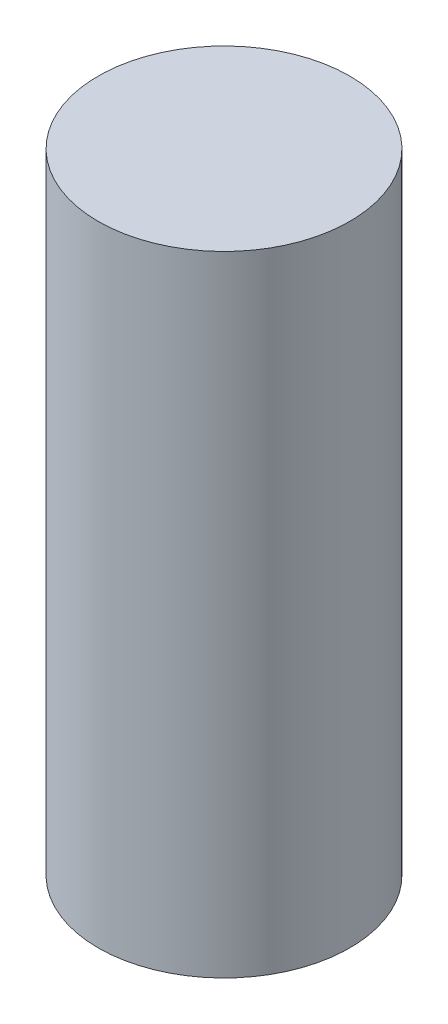
SolidWorks part; units mm, degrees
ref_plane "Alzado" through (0, 0, 0) normal (0, 0, 1) x (1, 0, 0)
ref_plane "Planta" through (0, 0, 0) normal (0, 1, 0) x (1, 0, 0)
ref_plane "Vista lateral" through (0, 0, 0) normal (1, 0, 0) x (0, 0, -1)
sketch "Croquis2" plane through (0, 0, 0) normal (0, 0, 1) x (1, 0, 0)
  line L1 (0, 0) -> (20, 0)
  line L2 (0, 0) -> (0, 100)
  line L3 (0, 100) -> (20, 100)
  line L4 (20, 0) -> (20, 100)
  dimension "D1" = 20
  dimension "D2" = 100
revolve "Revolución1" add sketch "Croquis2" angle 360 about L2
